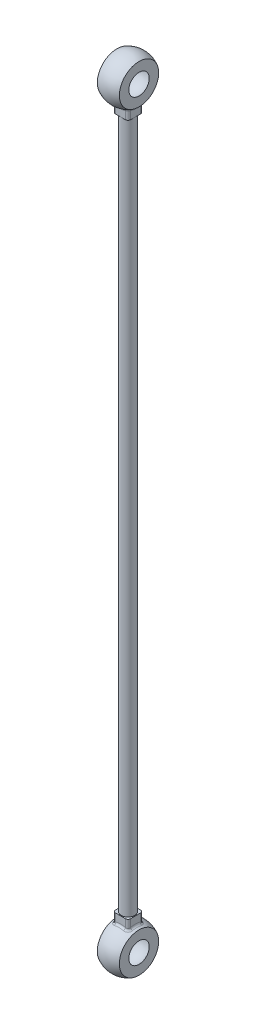
SolidWorks part; units mm, degrees
ref_plane "Plan de face" through (0, 0, 0) normal (0, 0, 1) x (1, 0, 0)
ref_plane "Plan de dessus" through (0, 0, 0) normal (0, 1, 0) x (1, 0, 0)
ref_plane "Plan de droite" through (0, 0, 0) normal (1, 0, 0) x (0, 0, -1)
sketch "Esquisse1" plane through (0, 0, 0) normal (0, 0, 1) x (1, 0, 0)
  line L0 (0, 6.1775) -> (0, -7.0511) construction
  line L1 (0, 4.5) -> (0, 3)
  line L2 (0, -3) -> (0, -4.5)
  arc A0 (0, 3) -> (0, -3) centre (0, 0) ccw
  arc A1 (0, 4.5) -> (0, -4.5) centre (0, 0) ccw
  dimension "D1" = 6
  dimension "D2" = 9
revolve "Révolution1" add sketch "Esquisse1" angle 360 about L0
sketch "Esquisse2" plane through (0, 0, 0) normal (0, 0, 1) x (1, 0, 0)
  line L0 (0, 4.7545) -> (0, -4.9673) construction
  line L1 (6.0193, 4.2729) -> (6.0193, -4.3737)
  line L2 (-6.0193, 4.2729) -> (-2.2, 4.2729)
  line L3 (-6.0193, 4.2729) -> (-6.0193, -4.3737)
  line L4 (-6.0193, -4.3737) -> (-2.2, -4.3737)
  line L5 (-2.2, 4.2729) -> (-2.2, -4.3737)
  line L6 (6.0193, -4.3737) -> (2.2, -4.3737)
  line L7 (2.2, 4.2729) -> (2.2, -4.3737)
  line L8 (6.0193, 4.2729) -> (2.2, 4.2729)
  dimension "D1" = 2.2
extrude "Enlèv. mat.-Extru.1" cut sketch "Esquisse2" against normal through all and the other way through all
sketch "Esquisse3" plane through (0, 0, 0) normal (1, 0, 0) x (0, 0, -1)
  line L0 (0, 0) -> (0, -7.3448) construction
  line L1 (-1.5, -3.5671) -> (1.5, -3.5671)
  line L2 (-1.5, -3.5671) -> (-1.5, -6)
  line L3 (-1.5, -6) -> (1.5, -6)
  line L4 (1.5, -3.5671) -> (1.5, -6)
  dimension "D1" = 1.5
  dimension "D2" = 1.5
  dimension "D3" = 6
extrude "Boss.-Extru.1" add sketch "Esquisse3" along normal blind 1.5 and the other way blind 1.5
sketch "Esquisse4" plane through (0, -6, 0) normal (0, -1, 0) x (1, 0, 0)
  circle A0 centre (0, 0) radius 1.35
  dimension "D1" = 2.7
extrude "Boss.-Extru.2" add sketch "Esquisse4" along normal blind 69
ref_plane "Plan1" through (0, -75, 0) normal (0, -1, 0) x (-1, 0, 0)
mirror "Symétrie11" about plane through (0, -75, 0) normal (0, -1, 0) of "Boss.-Extru.2"
mirror "Symétrie12" about plane through (0, -75, 0) normal (0, -1, 0) of "Boss.-Extru.1"
mirror "Symétrie13" about plane through (0, -75, 0) normal (0, -1, 0) of "Révolution1", "Symétrie12"
mirror "Symétrie14" about plane through (0, -75, 0) normal (0, -1, 0) of "Enlèv. mat.-Extru.1"
fillet "Congé1" radius 0.5 16 edges at (-1.5, -4.9843, -1.5) (-1.5, -4.9843, 1.5) (1.5, -4.9843, -1.5) (1.5, -4.9843, 1.5) (1.5, -4.2426, 0) (0, -4.2426, 1.5) (-1.5, -4.2426, 0) (0, -4.2426, -1.5) (1.5, -145.0157, 1.5) (1.5, -145.0157, -1.5) (-1.5, -145.0157, 1.5) (-1.5, -145.0157, -1.5) (-1.5, -145.7574, 0) (0, -145.7574, -1.5) (1.5, -145.7574, 0) (0, -145.7574, 1.5)
